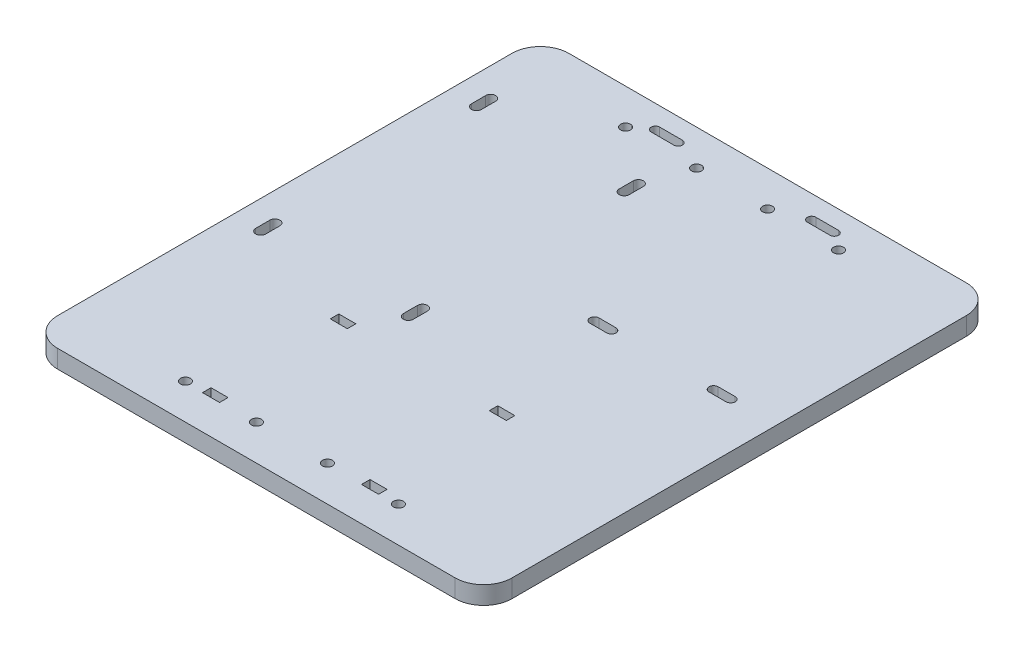
SolidWorks part; units mm, degrees
ref_plane "Front Plane" through (0, 0, 0) normal (0, 0, 1) x (1, 0, 0)
ref_plane "Top Plane" through (0, 0, 0) normal (0, 1, 0) x (1, 0, 0)
ref_plane "Right Plane" through (0, 0, 0) normal (1, 0, 0) x (0, 0, -1)
sketch "Sketch1" plane through (0, 0, 0) normal (0, 1, 0) x (1, 0, 0)
  line L1 (-10, 0) -> (-150, 0)
  line L2 (0, 10) -> (0, 170)
  line L3 (-10, 180) -> (-150, 180)
  line L4 (-160, 10) -> (-160, 170)
  arc A0 (-10, 0) -> (0, 10) centre (-10, 10) ccw
  arc A1 (-160, 10) -> (-150, 0) centre (-150, 10) ccw
  arc A2 (-160, 170) -> (-150, 180) centre (-150, 170) cw
  arc A3 (0, 170) -> (-10, 180) centre (-10, 170) ccw
  point P7 (0, 0)
  point P10 (-160, 0)
  point P13 (-160, 180)
  point P16 (0, 180)
  dimension "D3" = 10
  dimension "D1" = 160
  dimension "D2" = 180
extrude "main" add sketch "Sketch1" along normal blind 6.35
sketch "Sketch8" plane through (0, 0, 0) normal (0, -1, 0) x (1, 0, 0)
  line L0 (-98, -147.5) -> (-98, -152.5) construction
  line L1 (-98, -150) -> (-150, -150)
  line L2 (-98, -150) -> (-98, -74)
  line L3 (-98, -74) -> (-150, -74)
  line L4 (-150, -150) -> (-150, -74)
  line L5 (-96.25, -147.5) -> (-96.25, -152.5)
  line L6 (-99.75, -147.5) -> (-99.75, -152.5)
  line L7 (-124, -150) -> (-124, -74) construction
  line L8 (-98, -112) -> (-150, -112) construction
  line L9 (-98, -71.5) -> (-98, -76.5) construction
  line L10 (-96.25, -71.5) -> (-96.25, -76.5)
  line L11 (0, -170) -> (0, -10)
  line L12 (-10, 0) -> (-150, 0)
  line L13 (-160, -10) -> (-160, -170)
  line L14 (-150, -180) -> (-10, -180)
  line L15 (0, -170) -> (0, -10)
  line L16 (-10, 0) -> (-150, 0)
  line L17 (-160, -10) -> (-160, -170)
  line L18 (-150, -180) -> (-10, -180)
  line L19 (-99.75, -71.5) -> (-99.75, -76.5)
  line L21 (-150, -147.5) -> (-150, -152.5) construction
  line L22 (-148.25, -147.5) -> (-148.25, -152.5)
  line L23 (-151.75, -147.5) -> (-151.75, -152.5)
  line L24 (-150, -71.5) -> (-150, -76.5) construction
  line L25 (-148.25, -71.5) -> (-148.25, -76.5)
  line L26 (-151.75, -71.5) -> (-151.75, -76.5)
  line L27 (-150, -150) -> (-150, -74) [skipped]
  arc A0 (-96.25, -147.5) -> (-99.75, -147.5) centre (-98, -147.5) ccw
  arc A1 (-99.75, -152.5) -> (-96.25, -152.5) centre (-98, -152.5) ccw
  arc A2 (-96.25, -71.5) -> (-99.75, -71.5) centre (-98, -71.5) ccw
  arc A3 (-99.75, -76.5) -> (-96.25, -76.5) centre (-98, -76.5) ccw
  arc A4 (-148.25, -147.5) -> (-151.75, -147.5) centre (-150, -147.5) ccw
  arc A5 (-151.75, -152.5) -> (-148.25, -152.5) centre (-150, -152.5) ccw
  arc A6 (-148.25, -71.5) -> (-151.75, -71.5) centre (-150, -71.5) ccw
  arc A7 (-151.75, -76.5) -> (-148.25, -76.5) centre (-150, -76.5) ccw
  arc A12 (0, -10) -> (-10, 0) centre (-10, -10) ccw
  arc A13 (0, -10) -> (-10, 0) centre (-10, -10) ccw
  arc A14 (-150, 0) -> (-160, -10) centre (-150, -10) ccw
  arc A15 (-150, 0) -> (-160, -10) centre (-150, -10) ccw
  arc A16 (-160, -170) -> (-150, -180) centre (-150, -170) ccw
  arc A17 (-160, -170) -> (-150, -180) centre (-150, -170) ccw
  arc A18 (-10, -180) -> (0, -170) centre (-10, -170) ccw
  arc A19 (-10, -180) -> (0, -170) centre (-10, -170) ccw
  point P6 (-98, -150)
  point P20 (-98, -74)
  point P31 (-150, -150)
  point P37 (-150, -74)
  dimension "D1" = 3.5
  dimension "D2" = 52
  dimension "D3" = 76
  dimension "D4" = 5
  dimension "D6" = 10
  dimension "D7" = 30
  dimension "D5" = 0
  dimension "D8" = 2
extrude "odroid" cut sketch "Sketch8" against normal up to next contours L5 A1 L6 A0 | L23 A5 L22 A4 | L26 A7 L25 A6 | A2 L19 A3 L10
sketch "Sketch9" plane through (0, 0, 0) normal (0, -1, 0) x (1, 0, 0)
  line L4 (0, -170) -> (0, -10)
  line L5 (-10, 0) -> (-150, 0)
  line L6 (-160, -10) -> (-160, -170)
  line L7 (-150, -180) -> (-10, -180)
  line L8 (0, -170) -> (0, -10)
  line L9 (-10, 0) -> (-150, 0)
  line L10 (-160, -10) -> (-160, -170)
  line L11 (-150, -180) -> (-10, -180)
  line L12 (-58, -103) -> (-64, -103) construction
  line L13 (-58, -104.6) -> (-64, -104.6)
  line L14 (-58, -101.4) -> (-64, -101.4)
  line L15 (-96.25, -147.5) -> (-96.25, -152.5) construction
  line L16 (-16, -103) -> (-22, -103) construction
  line L17 (-16, -104.6) -> (-22, -104.6)
  line L18 (-16, -101.4) -> (-22, -101.4)
  line L19 (-19, -103) -> (-61, -103) construction
  arc A0 (-58, -104.6) -> (-58, -101.4) centre (-58, -103) ccw
  arc A1 (-64, -101.4) -> (-64, -104.6) centre (-64, -103) ccw
  arc A2 (-96.25, -147.5) -> (-99.75, -147.5) centre (-98, -147.5) ccw construction
  arc A3 (-16, -104.6) -> (-16, -101.4) centre (-16, -103) ccw
  arc A4 (-22, -101.4) -> (-22, -104.6) centre (-22, -103) ccw
  arc A9 (0, -10) -> (-10, 0) centre (-10, -10) ccw
  arc A10 (0, -10) -> (-10, 0) centre (-10, -10) ccw
  arc A11 (-150, 0) -> (-160, -10) centre (-150, -10) ccw
  arc A12 (-150, 0) -> (-160, -10) centre (-150, -10) ccw
  arc A13 (-160, -170) -> (-150, -180) centre (-150, -170) ccw
  arc A14 (-160, -170) -> (-150, -180) centre (-150, -170) ccw
  arc A15 (-10, -180) -> (0, -170) centre (-10, -170) ccw
  arc A16 (-10, -180) -> (0, -170) centre (-10, -170) ccw
  point P6 (-61, -103)
  point P13 (-96.25, -150)
  point P20 (-19, -103)
  dimension "D5" = 37
  dimension "D2" = 3.2
  dimension "D3" = 6
  dimension "D4" = 47
  dimension "D7" = 42
  dimension "D1" = 0
  dimension "D6" = 2
extrude "reg" cut sketch "Sketch9" against normal blind 6.35 contours L14 A1 L13 A0 | L18 A4 L17 A3
sketch "Sketch10" plane through (0, 0, 0) normal (0, -1, 0) x (1, 0, 0)
  line L0 (0, -90) -> (-160, -90)
  line L1 (-105, -60) -> (-105, -57)
  line L2 (-49, -60) -> (-55, -60)
  line L3 (-49, -60) -> (-49, -57)
  line L4 (-49, -57) -> (-55, -57)
  line L5 (-160, -170) -> (-160, -10) construction
  line L6 (0, -10) -> (0, -170) construction
  line L7 (-80, -180) -> (-80, 0) construction
  line L8 (-10, -180) -> (-150, -180) construction
  line L9 (-150, 0) -> (-10, 0) construction
  line L10 (-55, -60) -> (-55, -57)
  line L11 (-111, -57) -> (-105, -57)
  line L12 (-111, -60) -> (-111, -57)
  line L13 (-111, -60) -> (-105, -60)
  line L14 (-105, -15) -> (-105, -12)
  line L15 (-49, -15) -> (-55, -15)
  line L16 (-49, -15) -> (-49, -12)
  line L17 (-49, -12) -> (-55, -12)
  line L18 (-55, -15) -> (-55, -12)
  line L19 (-111, -12) -> (-105, -12)
  line L20 (-111, -15) -> (-111, -12)
  line L21 (-111, -15) -> (-105, -15)
  line L22 (-49, -57) -> (-49, -15) construction
  point P9 (-80, -90)
  dimension "D1" = 6
  dimension "D2" = 3
  dimension "D3" = 25
  dimension "D5" = 42
  dimension "D6" = 12
  dimension "D4" = 2
extrude "bat" cut sketch "Sketch10" against normal blind 6.35 contours L10 L2 L3 L4 | L20 L21 L14 L19 | L12 L13 L1 L11 | L15 L18 L17 L16
sketch "Sketch11" plane through (0, 0, 0) normal (0, -1, 0) x (1, 0, 0)
  line L0 (-67.5, -167.5) -> (-92.5, -167.5) construction
  line L3 (0, -90) -> (-160, -90) construction
  line L4 (0, -10) -> (0, -170) construction
  line L5 (-160, -170) -> (-160, -10) construction
  line L6 (-42.5, -167.5) -> (-117.5, -167.5) construction
  line L7 (-80, -180) -> (-80, 0) construction
  line L8 (-10, -180) -> (-150, -180) construction
  line L9 (-150, 0) -> (-10, 0) construction
  circle A0 centre (-67.5, -167.5) radius 1.75
  circle A1 centre (-42.5, -167.5) radius 1.75
  circle A3 centre (-117.5, -12.5) radius 1.75
  circle A4 centre (-92.5, -167.5) radius 1.75
  circle A5 centre (-92.5, -12.5) radius 1.75
  circle A8 centre (-42.5, -12.5) radius 1.75
  circle A9 centre (-67.5, -12.5) radius 1.75
  circle A11 centre (-117.5, -167.5) radius 1.75
  circle A12 centre (-17.5, -167.5) radius 1.75 [skipped]
  point P11 (0, 0)
  point P12 (-117.5, -167.5)
  point P24 (-92.5, -160.4168)
  point P25 (0, 0)
  point P32 (-80, -167.5)
  dimension "D1" = 3.5
  dimension "D5" = 25
  dimension "D4" = 155
  dimension "D3" = 25
  dimension "D2" = 3
extrude "mount" cut sketch "Sketch11" against normal blind 6.35
sketch "Sketch12" plane through (0, 0, 0) normal (0, -1, 0) x (1, 0, 0)
  line L0 (-48.5, -172) -> (-56.5, -172) construction
  line L1 (-48.5, -173.5) -> (-56.5, -173.5)
  line L2 (-48.5, -170.5) -> (-56.5, -170.5)
  line L3 (-80, -180) -> (-80, 0) construction
  line L4 (-10, -180) -> (-150, -180) construction
  line L5 (-150, 0) -> (-10, 0) construction
  line L6 (-111.5, -172) -> (-103.5, -172) construction
  line L7 (-111.5, -173.5) -> (-103.5, -173.5)
  line L8 (-111.5, -170.5) -> (-103.5, -170.5)
  arc A0 (-48.5, -173.5) -> (-48.5, -170.5) centre (-48.5, -172) ccw
  arc A1 (-56.5, -170.5) -> (-56.5, -173.5) centre (-56.5, -172) ccw
  arc A2 (-111.5, -173.5) -> (-111.5, -170.5) centre (-111.5, -172) cw
  arc A3 (-103.5, -170.5) -> (-103.5, -173.5) centre (-103.5, -172) cw
  point P2 (-52.5, -172)
  point P16 (-107.5, -172)
  dimension "D1" = 3
  dimension "D2" = 8
  dimension "D3" = 8
  dimension "D4" = 55
extrude "camera" cut sketch "Sketch12" against normal blind 6.35
